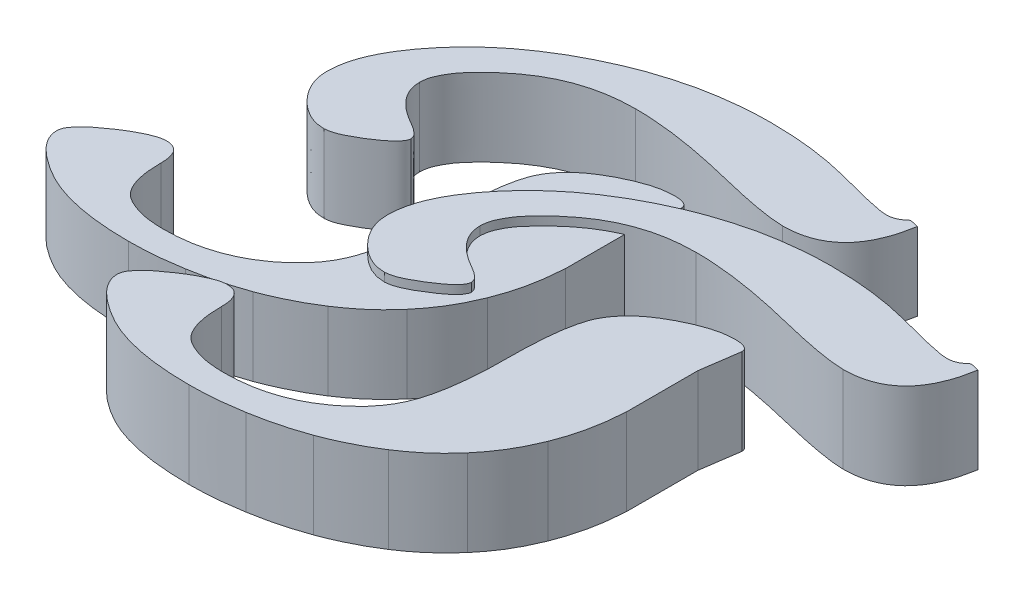
SolidWorks part; units mm, degrees
ref_plane "Front Plane" through (0, 0, 0) normal (0, 0, 1) x (1, 0, 0)
ref_plane "Top Plane" through (0, 0, 0) normal (0, 1, 0) x (1, 0, 0)
ref_plane "Right Plane" through (0, 0, 0) normal (1, 0, 0) x (0, 0, -1)
sketch "Sketch1" plane through (0, 0, 0) normal (0, 1, 0) x (1, 0, 0)
  text T0 "T" font "Script MT Bold" height in points 200
extrude "Boss-Extrude2" add sketch "Sketch1" along normal blind 10
sketch "Sketch2" plane through (0, 0, 0) normal (0, 1, 0) x (1, 0, 0)
  text T0 "T" font "Script MT Bold" height in points 200
extrude "Boss-Extrude3" add sketch "Sketch2" along normal blind 9 separate body
